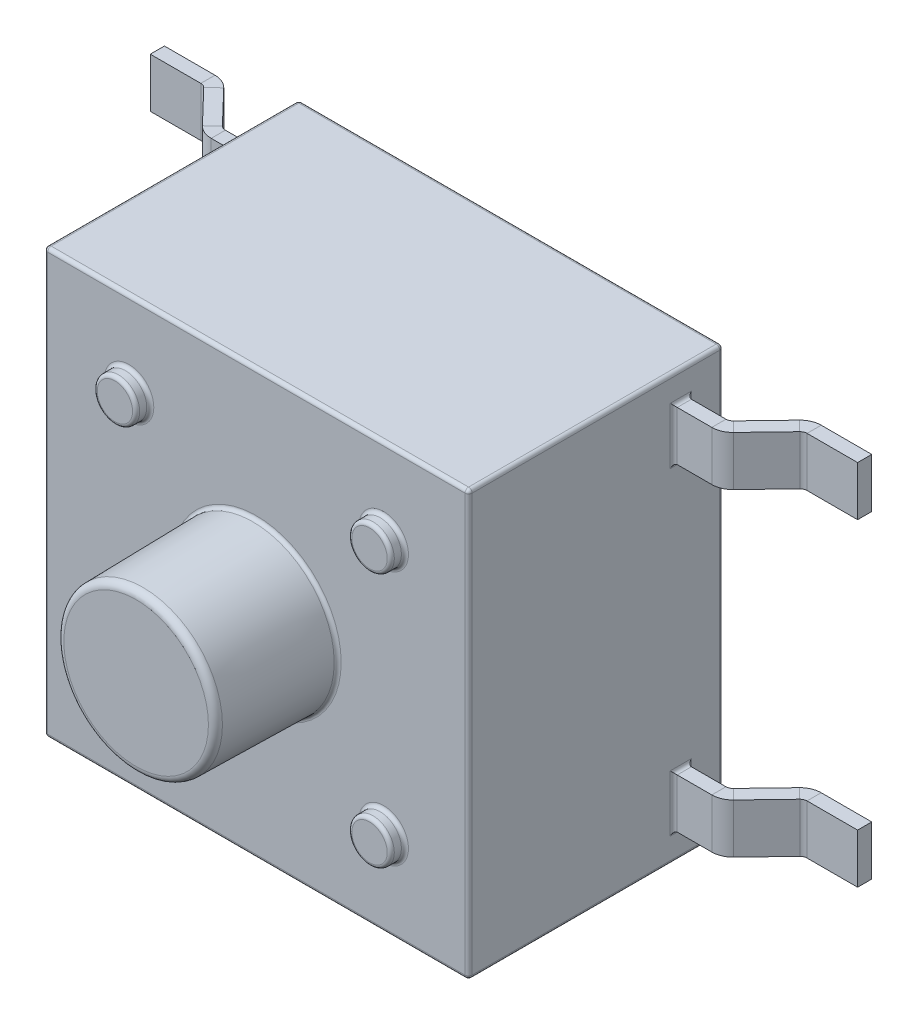
SolidWorks part; units mm, degrees
ref_plane "Front Plane" through (0, 0, 0) normal (0, 0, 1) x (1, 0, 0)
ref_plane "Top Plane" through (0, 0, 0) normal (0, 1, 0) x (1, 0, 0)
ref_plane "Right Plane" through (0, 0, 0) normal (1, 0, 0) x (0, 0, -1)
sketch "Sketch1" plane through (0, 0, 0) normal (0, 0, 1) x (1, 0, 0)
  line L1 (-3, 3) -> (3, 3)
  line L2 (-3, 3) -> (-3, -3)
  line L3 (-3, -3) -> (3, -3)
  line L4 (3, 3) -> (3, -3)
  line L5 (-3, 3) -> (3, -3) construction
  line L6 (-3, -3) -> (3, 3) construction
  point P0 (0, 0)
  dimension "D1" = 6
  dimension "D2" = 6
extrude "Boss-Extrude1" add sketch "Sketch1" along normal blind 3.3
sketch "Sketch2" plane through (0, 0, 3.3) normal (0, 0, 1) x (1, 0, 0)
  line L1 (-3, 3) -> (3, 3)
  line L2 (-3, 3) -> (-3, -3)
  line L3 (-3, -3) -> (3, -3)
  line L4 (3, 3) -> (3, -3)
  line L5 (-3, 3) -> (3, -3) construction
  line L6 (-3, -3) -> (3, 3) construction
  point P0 (0, 0)
extrude "Boss-Extrude2" add sketch "Sketch2" along normal blind 0.3
sketch "Sketch3" plane through (0, 0, 3.6) normal (0, 0, 1) x (1, 0, 0)
  line L0 (0, 4.3748) -> (0, -3.2039) construction
  line L1 (5.0333, 0) -> (-6.3552, 0) construction
  circle A0 centre (-1.8, 1.8) radius 0.3
  circle A1 centre (1.8, 1.8) radius 0.3
  circle A2 centre (1.8, -1.8) radius 0.3
  circle A3 centre (-1.8, -1.8) radius 0.3
  dimension "D1" = 0.6
  dimension "D2" = 1.8
  dimension "D3" = 1.8
extrude "Boss-Extrude3" add sketch "Sketch3" along normal blind 0.2
sketch "Sketch4" plane through (0, 0, 3.6) normal (0, 0, 1) x (1, 0, 0)
  circle A0 centre (0, 0) radius 1.15
  dimension "D1" = 2.3
extrude "Boss-Extrude4" add sketch "Sketch4" along normal blind 1.7 draft 1
sketch "Sketch5" plane through (0, 0, 0) normal (0, 1, 0) x (1, 0, 0)
  line L0 (3, -0.6) -> (3.5389, -0.6)
  line L1 (3, -3.6) -> (3, 0) construction
  line L2 (3.6832, -0.5385) -> (4.141, -0.0615)
  line L3 (4.2853, 0) -> (5, 0)
  line L4 (3, 0) -> (-3, 0) construction
  arc A0 (4.2853, 0) -> (4.141, -0.0615) centre (4.2853, -0.2) ccw
  arc A1 (3.5389, -0.6) -> (3.6832, -0.5385) centre (3.5389, -0.4) ccw
  point P1 (3.6241, -0.6)
  point P10 (4.2, 0)
  dimension "D2" = 0.2
  dimension "D1" = 5
  dimension "D3" = 0.6
  dimension "D4" = 4.2
sketch "Sketch6" plane through (3, 0, 0) normal (1, 0, 0) x (0, 0, -1)
  line L0 (0, -3) -> (0, 3) construction
  line L2 (-0.7, 2.6) -> (-0.5, 2.6)
  line L3 (-0.7, 2.6) -> (-0.7, 1.9)
  line L4 (-0.7, 1.9) -> (-0.5, 1.9)
  line L5 (-0.5, 2.6) -> (-0.5, 1.9)
  line L6 (-0.7, 2.6) -> (-0.5, 1.9) construction
  line L7 (-0.7, 1.9) -> (-0.5, 2.6) construction
  point P3 (-0.6, 2.25)
  dimension "D1" = 0.2
  dimension "D2" = 0.7
  dimension "D3" = 2.25
  dimension "D4" = 0.6
sweep "Sweep4" add profiles "Sketch6" path "Sketch5"
mirror "Mirror1" about plane through (0, 0, 0) normal (0, 1, 0) of "Sweep4"
mirror "Mirror2" about plane through (0, 0, 0) normal (1, 0, 0) of "Sweep4", "Mirror1"
fillet "Fillet1" radius 0.1 1 edges at (1.1203, 0, 5.3)
fillet "Fillet2" radius 0.05 4 edges at (2.1, -1.8, 3.8) (-2.1, -1.8, 3.8) (1.5, 1.8, 3.8) (-1.5, 1.8, 3.8)
fillet "Fillet3" radius 0.05 33 edges at (-3, 0, 0) (-3, 2.25, 0.7) (-3, 2.6, 0.6) (-3, 2.25, 0.5) (-3, 1.9, 0.6) (-3, -2.25, 0.5) (-3, -2.6, 0.6) (-3, -2.25, 0.7) (-3, -1.9, 0.6) (-3, -3, 1.8) (0, -3, 0) (3, -3, 1.8) (3, 0, 0) (3, 2.25, 0.5) (3, 2.6, 0.6) (3, 2.25, 0.7) (3, 1.9, 0.6) (3, -2.25, 0.7) (3, -2.6, 0.6) (3, -2.25, 0.5) (3, -1.9, 0.6) (3, 3, 1.8) (-3, 3, 1.8) (0, 3, 0) (0, -3, 3.6) (-3, 0, 3.6) (0, 3, 3.6) (3, 0, 3.6) (-1.5, 1.8, 3.6) (1.5, 1.8, 3.6) (2.1, -1.8, 3.6) (-2.1, -1.8, 3.6) (1.15, 0, 3.6)
